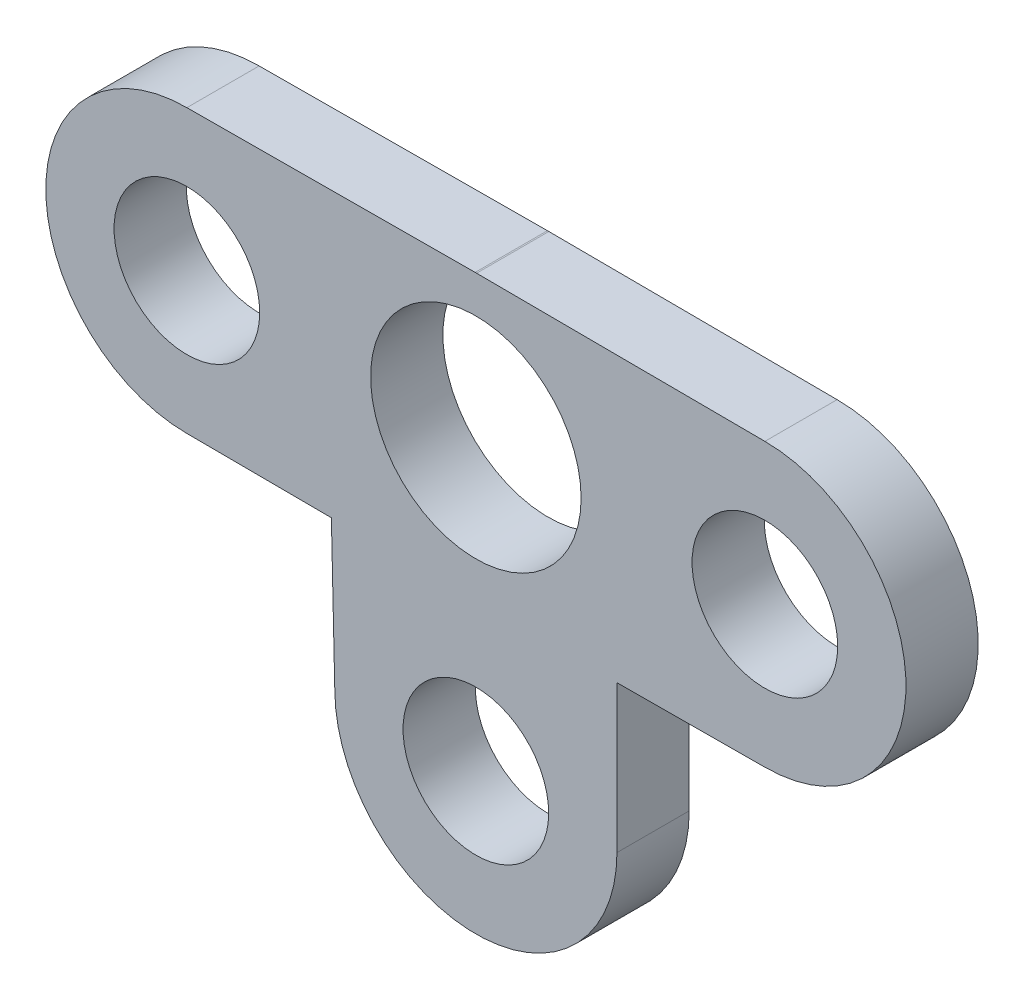
SolidWorks part; units mm, degrees
material "6061 Alloy"
ref_plane "Front Plane" through (0, 0, 0) normal (0, 0, 1) x (1, 0, 0)
ref_plane "Top Plane" through (0, 0, 0) normal (0, 1, 0) x (1, 0, 0)
ref_plane "Right Plane" through (0, 0, 0) normal (1, 0, 0) x (0, 0, -1)
sketch "Sketch3" plane through (0, 0, 0) normal (0, 0, 1) x (1, 0, 0)
  line L0 (0, 6.2651) -> (12.7, 6.2)
  line L1 (0, -6.2651) -> (12.7, -6.2)
  line L2 (-12.7, 6.2) -> (0, 6.2651)
  line L3 (0, -6.2651) -> (-12.7, -6.2)
  line L4 (-6.2, -12.7) -> (-6.35, -6.2325)
  line L5 (6.2, -12.7) -> (6.2, -6.2333)
  circle A1 centre (12.7, 0) radius 3.2
  circle A2 centre (-12.7, 0) radius 3.2
  circle A8 centre (0, 0) radius 6.265
  circle A9 centre (0, -12.7) radius 3.2
  arc A10 (-12.7, 6.2) -> (-12.7, -6.2) centre (-12.7, 0) ccw
  arc A11 (12.7, -6.2) -> (12.7, 6.2) centre (12.7, 0) ccw
  circle A13 centre (0, -12.7) radius 6.2
  circle A14 centre (0, 0) radius 4.625
  dimension "D3" = 6.4
  dimension "D4" = 12.53
  dimension "9.25" = 9.25
  dimension "D1" = 12.7
  dimension "D2" = 12.7
  dimension "D5" = 3
  dimension "D6" = 12.7
extrude "Boss-Extrude1" add sketch "Sketch3" along normal blind 3.175 contours A11 L0 A8 L1 | A10 L3 A8 L2 | A11 A1 | A10 A2 | A8 A14 | A13 L5 L1 L3 L4 | A13 A9
equation "\"D2@Sketch3\"=\"D1@Sketch3\""
